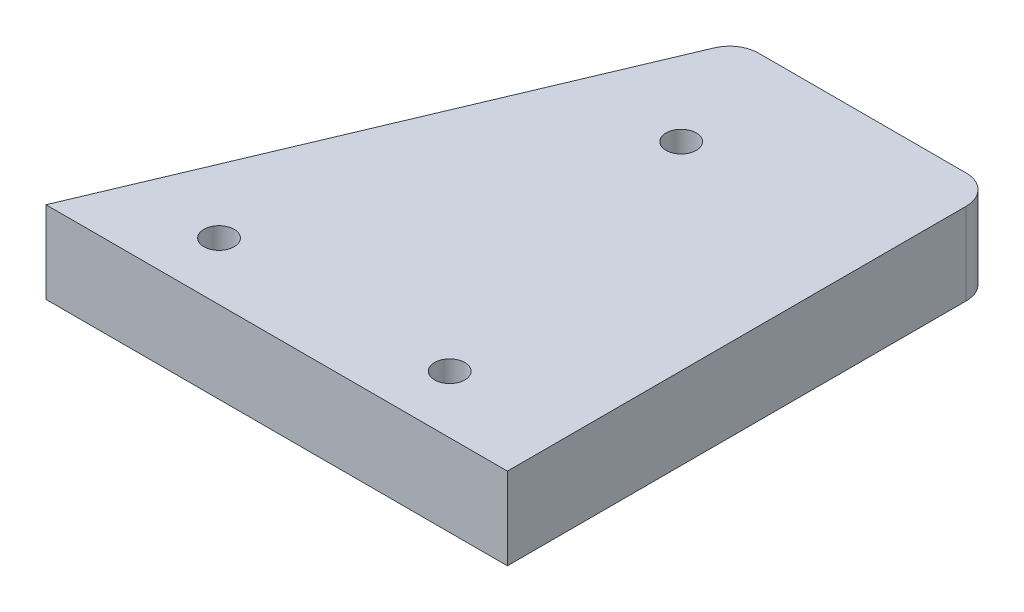
SolidWorks part; units mm, degrees
ref_plane "Front Plane" through (0, 0, 0) normal (0, 0, 1) x (1, 0, 0)
ref_plane "Top Plane" through (0, 0, 0) normal (0, 1, 0) x (1, 0, 0)
ref_plane "Right Plane" through (0, 0, 0) normal (1, 0, 0) x (0, 0, -1)
sketch "Sketch1" plane through (0, 0, 0) normal (0, 1, 0) x (1, 0, 0)
  line L0 (0, 0) -> (64, 0)
  line L1 (64, 0) -> (64, 67.63)
  line L2 (64, 67.63) -> (28.5335, 67.63)
  line L3 (28.5335, 67.63) -> (0, 0)
  line L4 (38.4754, 56.3704) -> (19474.7347, 46124.0578) construction
  line L5 (-32.9514, -8.75) -> (49967.0486, -8.75) construction
  line L6 (36.4754, 51.63) -> (12805.7192, -48290.3436) construction
  line L7 (16, 8) -> (50016, 8) construction
  line L8 (36.4754, 51.63) -> (-21205.4878, -45211.81) construction
  line L9 (16, 2) -> (50016, 2) construction
  line L10 (31.0438, 54.179) -> (-21210.9194, -45209.261) construction
  line L11 (30.6744, 50.0977) -> (12799.9182, -48291.8759) construction
  line L12 (16, 14) -> (50016, 14) construction
  line L13 (41.907, 49.081) -> (-21200.0562, -45214.359) construction
  line L14 (42.2764, 53.1623) -> (12811.5203, -48288.8113) construction
  circle A0 centre (16, 8) radius 2.1
  circle A1 centre (48, 8) radius 2.1
  circle A2 centre (36.4754, 51.63) radius 2.1
  circle A3 centre (48, -8.75) radius 2.1 construction
  dimension "D1" = 4.2
  dimension "D7" = 4.2
  dimension "D2" = 8
  dimension "D3" = 32
  dimension "D4" = 16
  dimension "D5" = 67.125
  dimension "D6" = 60.38
  dimension "D8" = 16
  dimension "D9" = 8.75
  dimension "D10" = 61.47
  dimension "D11" = 16
  dimension "D12" = 6
  dimension "D13" = 6
extrude "Boss-Extrude1" add sketch "Sketch1" along normal blind 11.38
fillet "Fillet1" radius 4 2 edges at (64, 5.69, -67.63) (28.5335, 5.69, -67.63)
